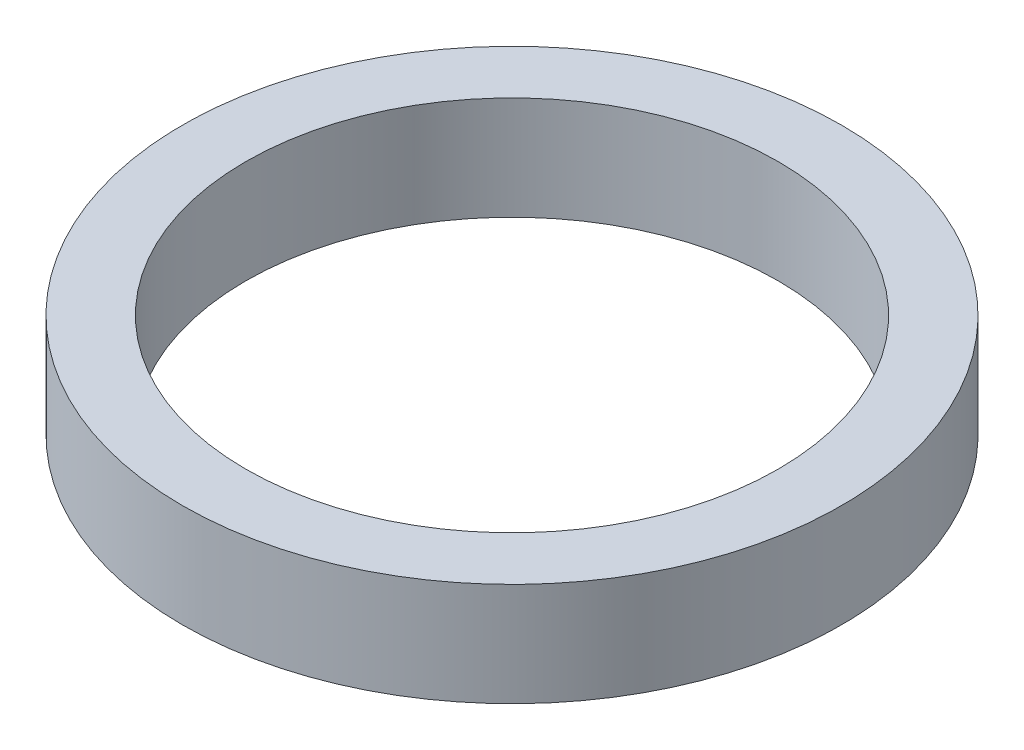
SolidWorks part; units mm, degrees
ref_plane "Front Plane" through (0, 0, 0) normal (0, 0, 1) x (1, 0, 0)
ref_plane "Top Plane" through (0, 0, 0) normal (0, 1, 0) x (1, 0, 0)
ref_plane "Right Plane" through (0, 0, 0) normal (1, 0, 0) x (0, 0, -1)
sketch "Sketch1" plane through (0, 0, 0) normal (0, 1, 0) x (1, 0, 0)
  circle A0 centre (0, 0) radius 12.63
  circle A1 centre (0, 0) radius 15.63
  dimension "D1" = 25.26
  dimension "D2" = 3
extrude "Boss-Extrude1" add sketch "Sketch1" along normal blind 4.9
